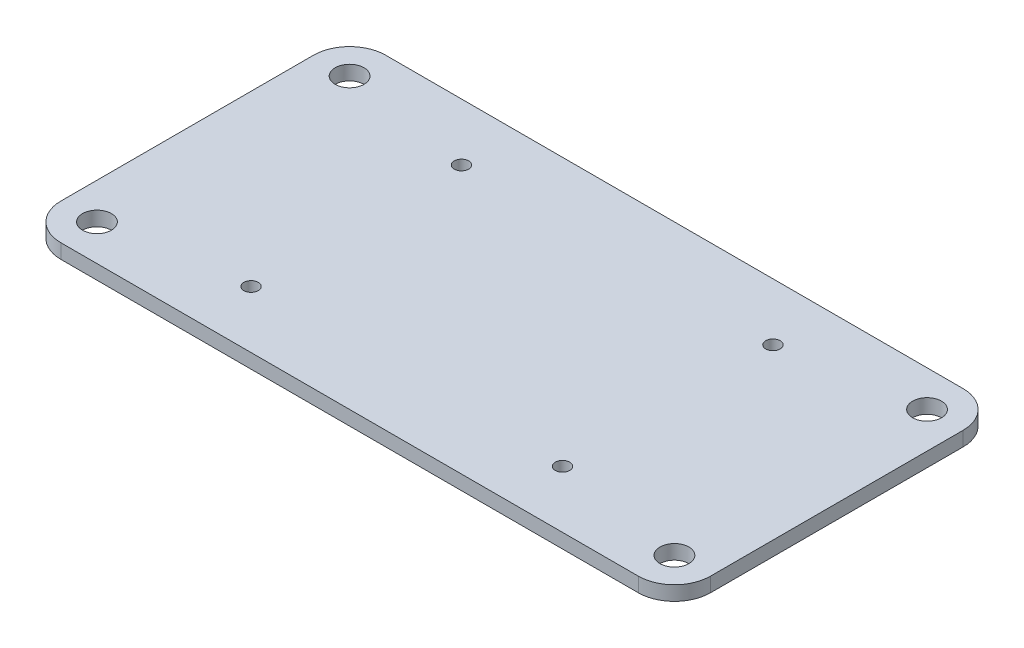
SolidWorks part; units mm, degrees
ref_plane "Alzado" through (0, 0, 0) normal (0, 0, 1) x (1, 0, 0)
ref_plane "Planta" through (0, 0, 0) normal (0, 1, 0) x (1, 0, 0)
ref_plane "Vista lateral" through (0, 0, 0) normal (1, 0, 0) x (0, 0, -1)
sketch "Croquis2" plane through (0, 0, 0) normal (0, 1, 0) x (1, 0, 0)
  line L1 (-90, -45) -> (90, -45)
  line L2 (-90, -45) -> (-90, 45)
  line L3 (-90, 45) -> (90, 45)
  line L4 (90, -45) -> (90, 45)
  line L5 (-90, -45) -> (90, 45) construction
  line L6 (-90, 45) -> (90, -45) construction
  point P0 (0, 0)
  dimension "D1" = 90
  dimension "D2" = 180
extrude "Saliente-Extruir1" add sketch "Croquis2" along normal blind 4
fillet "Redondeo1" radius 10 4 edges at (90, 2, 45) (90, 2, -45) (-90, 2, -45) (-90, 2, 45)
sketch "Croquis4" plane through (0, 4, 0) normal (0, 1, 0) x (1, 0, 0)
  line L0 (0, 0) -> (0, 59.7635) construction
  circle A0 centre (-80, 35) radius 4
  circle A1 centre (-80, -35) radius 4
  circle A4 centre (80, -35) radius 4
  circle A5 centre (80, 35) radius 4
  dimension "D1" = 8
extrude "Cortar-Extruir2" cut sketch "Croquis4" against normal up to next
sketch "Croquis5" plane through (0, 4, 0) normal (0, 1, 0) x (1, 0, 0)
  line L0 (-90, 0) -> (90, 0) construction
  line L1 (-90, 35) -> (-90, -35) construction
  line L2 (90, -35) -> (90, 35) construction
  line L3 (0, 45) -> (0, -45) construction
  line L4 (80, 45) -> (-80, 45) construction
  line L5 (-80, -45) -> (80, -45) construction
  line L7 (-48, -33.75) -> (48, -33.75) construction
  line L8 (-48, -33.75) -> (-48, 33.75) construction
  line L9 (-48, 33.75) -> (48, 33.75) construction
  line L10 (48, -33.75) -> (48, 33.75) construction
  line L11 (-48, -33.75) -> (48, 33.75) construction
  line L12 (-48, 33.75) -> (48, -33.75) construction
  circle A0 centre (-43.15, 29.15) radius 2
  circle A1 centre (-43.15, -29.15) radius 2
  circle A2 centre (43.15, -29.15) radius 2
  circle A3 centre (43.15, 29.15) radius 2
  point P12 (0, 0)
  dimension "D3" = 4
  dimension "D4" = 4
  dimension "D1" = 67.5
  dimension "D2" = 96
  dimension "D5" = 29.15
  dimension "D6" = 29.15
  dimension "D7" = 43.15
extrude "Cortar-Extruir3" cut sketch "Croquis5" against normal up to next
